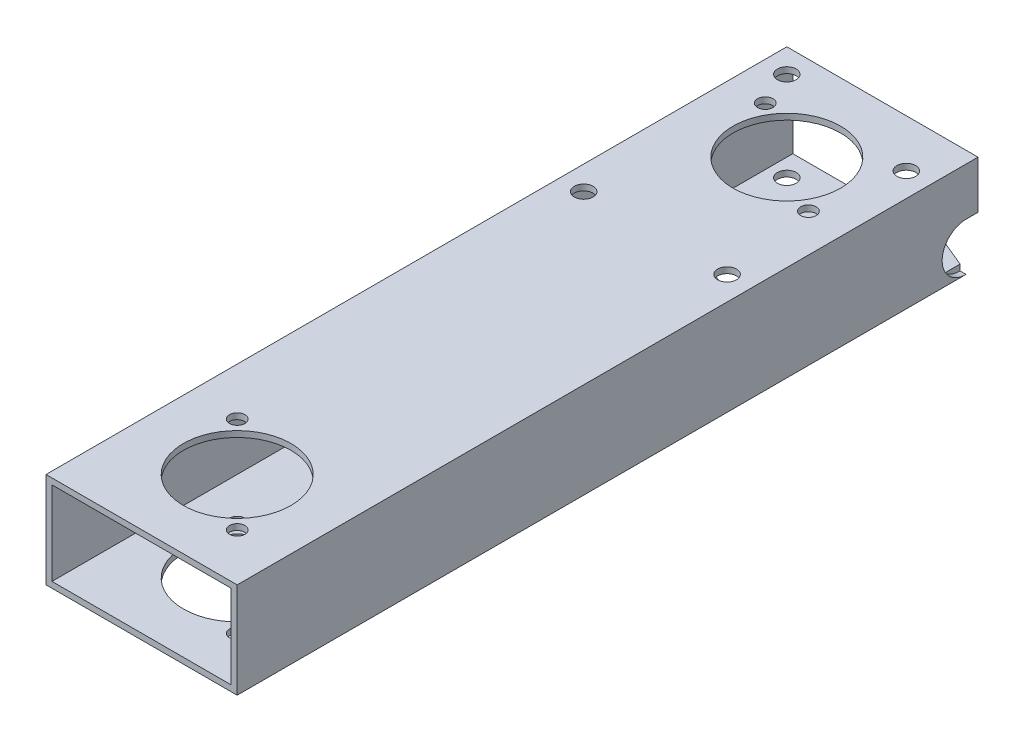
SolidWorks part; units mm, degrees
material "6061 Alloy"
ref_plane "Front Plane" through (0, 0, 0) normal (0, 0, 1) x (1, 0, 0)
ref_plane "Top Plane" through (0, 0, 0) normal (0, 1, 0) x (1, 0, 0)
ref_plane "Right Plane" through (0, 0, 0) normal (1, 0, 0) x (0, 0, -1)
sketch "Sketch1" plane through (0, 0, 0) normal (0, 0, 1) x (1, 0, 0)
  line L0 (-23.8125, 11.1125) -> (23.8125, 11.1125)
  line L2 (-25.4, 12.7) -> (25.4, 12.7)
  line L3 (-25.4, 12.7) -> (-25.4, -12.7)
  line L4 (-25.4, -12.7) -> (25.4, -12.7)
  line L5 (25.4, 12.7) -> (25.4, -12.7)
  line L10 (23.8125, 11.1125) -> (23.8125, -11.1125)
  line L11 (-23.8125, -11.1125) -> (23.8125, -11.1125)
  line L12 (-23.8125, 11.1125) -> (-23.8125, -11.1125)
  point P12 (0, 12.7)
  point P14 (25.4, 0)
  dimension "Wall Thickness" = 1.5875
  dimension "Outside Width" = 50.8
  dimension "Outside Height" = 25.4
  dimension "Inside Height" = 22.225
  dimension "Inside Width" = 47.625
sketch "Sketch2" plane through (0, 0, 0) normal (1, 0, 0) x (0, 0, -1)
  line L0 (98.425, 0) -> (-98.425, 0)
  point P4 (0, 0)
  point P7 (-98.425, 0)
  point P10 (98.425, 0)
  dimension "Length" = 196.85
sketch "Sketch3" plane through (0, 0, 0) normal (0, 0, 1) x (1, 0, 0)
  line L21 (25.4, 12.7) -> (-25.4, 12.7)
  line L22 (25.4, -12.7) -> (25.4, 12.7)
  line L23 (-25.4, -12.7) -> (25.4, -12.7)
  line L24 (-25.4, 12.7) -> (-25.4, -12.7)
  line L25 (25.4, 12.7) -> (-25.4, 12.7)
  line L26 (25.4, -12.7) -> (25.4, 12.7)
  line L27 (-25.4, -12.7) -> (25.4, -12.7)
  line L28 (-25.4, 12.7) -> (-25.4, -12.7)
  line L29 (23.8125, 11.1125) -> (-23.8125, 11.1125)
  line L30 (23.8125, -11.1125) -> (23.8125, 11.1125)
  line L31 (-23.8125, -11.1125) -> (23.8125, -11.1125)
  line L32 (-23.8125, 11.1125) -> (-23.8125, -11.1125)
  line L33 (23.8125, 11.1125) -> (-23.8125, 11.1125)
  line L34 (23.8125, -11.1125) -> (23.8125, 11.1125)
  line L35 (-23.8125, -11.1125) -> (23.8125, -11.1125)
  line L36 (-23.8125, 11.1125) -> (-23.8125, -11.1125)
  dimension "D1" = 0
  dimension "D2" = 0
extrude "Boss-Extrude1" add sketch "Sketch3" along normal up to vertex (98.425 mm away) and the other way up to vertex (98.425 mm away) up to point (0, 0, 98.425) other way up to point (0, 0, -98.425)
sketch "Drawing Reference" plane through (0, 0, 0) normal (1, 0, 0) x (0, 0, -1)
  line L0 (-98.425, 0) -> (98.425, 0) construction
  line L1 (0, -12.7) -> (0, 12.7) construction
  line L2 (-98.425, -12.7) -> (98.425, -12.7) construction
  line L5 (-98.425, 12.7) -> (98.425, 12.7) construction
  point P7 (-61.849, 0)
  point P8 (61.849, 0)
  dimension "D1" = 36.576
sketch "Sketch4" plane through (0, -12.7, 0) normal (0, -1, 0) x (1, 0, 0)
  line L0 (-25.4, 0) -> (0, 0) construction
  line L1 (-25.4, 98.425) -> (-25.4, -98.425) construction
  line L2 (0, 0) -> (0, -73.025) construction
  line L3 (0, 0) -> (0, 73.025) construction
  circle A0 centre (0, 73.025) radius 14.2875
  circle A1 centre (0, -73.025) radius 14.2875
extrude "Cut-Extrude3" cut sketch "Sketch4" against normal through all
sketch "Sketch5" plane through (25.4, 0, 0) normal (1, 0, 0) x (0, 0, -1)
  line L7 (98.425, -12.7) -> (98.425, 12.7) construction
  line L8 (98.425, 0) -> (98.425, -12.7)
  line L9 (98.425, -12.7) -> (95.25, -12.7)
  line L10 (95.25, 0) -> (98.425, 0)
  arc A0 (95.25, 0) -> (95.25, -12.7) centre (95.25, -6.35) ccw
  dimension "D1" = 6.35
extrude "Cut-Extrude5" cut sketch "Sketch5" against normal blind 1.5875
sketch "Sketch6" plane through (0, -12.7, 0) normal (0, -1, 0) x (1, 0, 0)
  line L0 (23.8125, -98.425) -> (23.8125, -95.25)
  line L1 (23.8125, -95.25) -> (16.1925, -98.425)
  line L2 (-25.4, -98.425) -> (23.8125, -98.425) construction
  line L3 (16.1925, -98.425) -> (23.8125, -98.425)
  dimension "D1" = 7.62
extrude "Cut-Extrude6" cut sketch "Sketch6" against normal blind 1.5875
hole_wizard "#10 Clearance Hole1" positions "Sketch7" profile "Sketch8" hole size "#10" standard "ANSI Inch" end condition through all
sketch "Sketch7" plane through (0, -12.7, 0) normal (0, -1, 0) x (-1, 0, 0)
  point P0 (-19.05, 85.725)
  point P3 (19.05, 92.075)
  point P6 (19.05, 38.1)
  point P9 (-19.05, 38.1)
sketch "Sketch8" plane through (19.05, -12.7, -85.725) normal (1, 0, 0) x (0, 0, -1)
  line L0 (0, 0) -> (0, 25.4)
  line L1 (0, 25.4) -> (2.4892, 25.4)
  line L2 (2.4892, 25.4) -> (2.4892, 0)
  line L5 (2.4892, 0) -> (0, 0)
  line L11 (0, -6.35) -> (0, 107.95) construction
  dimension "Thru Hole Dia." = 4.9784
  dimension "Thru Hole Depth" = 25.4
hole_wizard "#20 (0.161) Diameter Hole1" positions "Sketch9" profile "Sketch10" hole size "#20" standard "ANSI Inch" end condition through all
sketch "Sketch9" plane through (0, -12.7, 0) normal (0, -1, 0) x (-1, 0, 0)
  point P0 (15.2937, 82.5816)
  point P3 (-15.2937, 63.4684)
sketch "Sketch10" plane through (-15.2937, -12.7, -82.5816) normal (1, 0, 0) x (0, 0, -1)
  line L0 (0, 0) -> (0, 25.4)
  line L1 (0, 25.4) -> (2.0447, 25.4)
  line L2 (2.0447, 25.4) -> (2.0447, 0)
  line L5 (2.0447, 0) -> (0, 0)
  line L11 (0, -6.35) -> (0, 107.95) construction
  dimension "Thru Hole Dia." = 4.0894
  dimension "Thru Hole Depth" = 25.4
sketch "Sketch11" plane through (0, 12.7, 0) normal (0, 1, 0) x (1, 0, 0)
  line L0 (0, -73.025) -> (-12.752, -60.273) construction
  line L1 (0, -73.025) -> (12.752, -85.777) construction
hole_wizard "#20 (0.161) Diameter Hole2" positions "Sketch12" profile "Sketch13" hole size "#20" standard "ANSI Inch" end condition through all
sketch "Sketch12" plane through (0, 12.7, 0) normal (0, 1, 0) x (1, 0, 0)
  point P0 (-12.752, -60.273)
  point P3 (12.752, -85.777)
sketch "Sketch13" plane through (-12.752, 12.7, 60.273) normal (1, 0, 0) x (0, 0, 1)
  line L0 (0, 0) -> (0, 25.4)
  line L1 (0, 25.4) -> (2.0447, 25.4)
  line L2 (2.0447, 25.4) -> (2.0447, 0)
  line L5 (2.0447, 0) -> (0, 0)
  line L11 (0, -6.35) -> (0, 107.95) construction
  dimension "Thru Hole Dia." = 4.0894
  dimension "Thru Hole Depth" = 25.4
equation "\"D1@Drawing Reference\"=\"Outside Width@Sketch1\" * 0.72"
